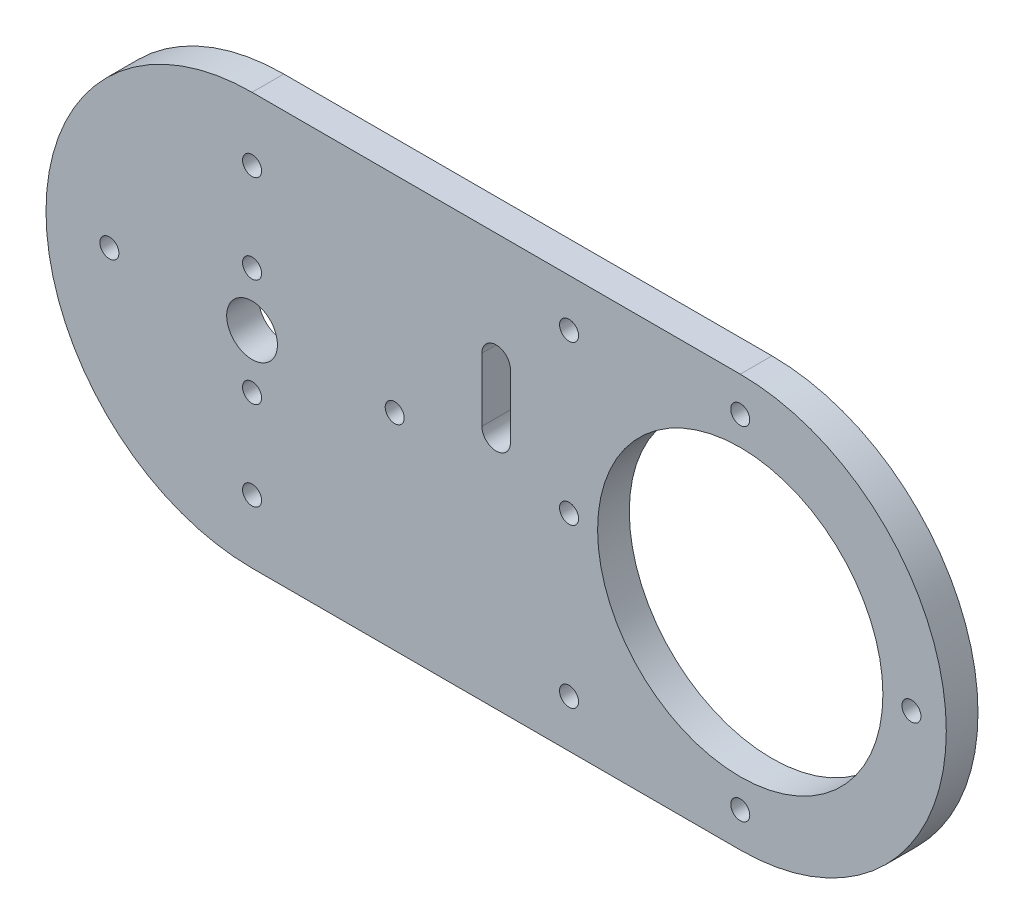
SolidWorks part; units mm, degrees
ref_plane "Front Plane" through (0, 0, 0) normal (0, 0, 1) x (1, 0, 0)
ref_plane "Top Plane" through (0, 0, 0) normal (0, 1, 0) x (1, 0, 0)
ref_plane "Right Plane" through (0, 0, 0) normal (1, 0, 0) x (0, 0, -1)
sketch "Sketch1" plane through (0, 0, 0) normal (0, 0, 1) x (1, 0, 0)
  line L0 (-38.5, 0) -> (38.5, 0) construction
  line L2 (-38.5, 32.5) -> (38.5, 32.5)
  line L3 (-38.5, -32.5) -> (38.5, -32.5)
  line L4 (-38.5, 0) -> (-38.5, 8.5) construction
  line L6 (-38.5, 0) -> (-38.5, -8.5) construction
  line L8 (-38.5, 0) -> (-38.5, 5) construction
  line L9 (-38.5, 5) -> (-2.25, 5) construction
  line L13 (0, 5) -> (0, 15) construction
  line L15 (-2.25, 5) -> (-2.25, 15)
  line L16 (2.25, 5) -> (2.25, 15)
  arc A0 (-38.5, 32.5) -> (-38.5, -32.5) centre (-38.5, 0) ccw
  arc A1 (38.5, -32.5) -> (38.5, 32.5) centre (38.5, 0) ccw
  circle A2 centre (-38.5, 0) radius 4
  circle A3 centre (38.5, 0) radius 22.5
  circle A11 centre (-38.5, 22.5) radius 1.5
  circle A12 centre (-16, 0) radius 1.5
  circle A13 centre (-38.5, -22.5) radius 1.5
  circle A14 centre (-61, 0) radius 1.5
  circle A16 centre (11.5, 0) radius 1.5
  circle A17 centre (11.5, -25) radius 1.5
  circle A19 centre (11.5, 25) radius 1.5
  circle A26 centre (65.5, 0) radius 1.5
  circle A27 centre (-38.5, 8.5) radius 1.5
  circle A28 centre (-38.5, -8.5) radius 1.5
  arc A29 (-2.25, 5) -> (2.25, 5) centre (0, 5) ccw
  arc A30 (2.25, 15) -> (-2.25, 15) centre (0, 15) ccw
  circle A31 centre (38.5, 27) radius 1.5
  circle A32 centre (38.5, -27) radius 1.5
  point P5 (0, 0)
  point P38 (0, 10)
  dimension "D5" = 3
  dimension "D6" = 8.5
  dimension "D7" = 45
  dimension "D8" = 8
  dimension "D9" = 8.5
  dimension "D13" = 36.25
  dimension "D14" = 4.5
  dimension "D15" = 10
  dimension "D16" = 27
  dimension "D17" = 22.5
  dimension "D21" = 3
  dimension "D22" = 3
  dimension "D23" = 3
  dimension "D24" = 3
  dimension "D25" = 27
  dimension "D26" = 7.5
  dimension "D27" = 3
  dimension "D28" = 3
  dimension "D29" = 7.5
  dimension "D30" = 3
  dimension "D31" = 27
  dimension "D32" = 3
  dimension "D33" = 3
  dimension "D4" = 27
  dimension "D10" = 3
  dimension "D11" = 3
  dimension "D1" = 77
  dimension "D2" = 65
  dimension "D12" = 5
  dimension "D18" = 22.5
  dimension "D19" = 22.5
  dimension "D20" = 22.5
extrude "Boss-Extrude1" add sketch "Sketch1" along normal blind 5
